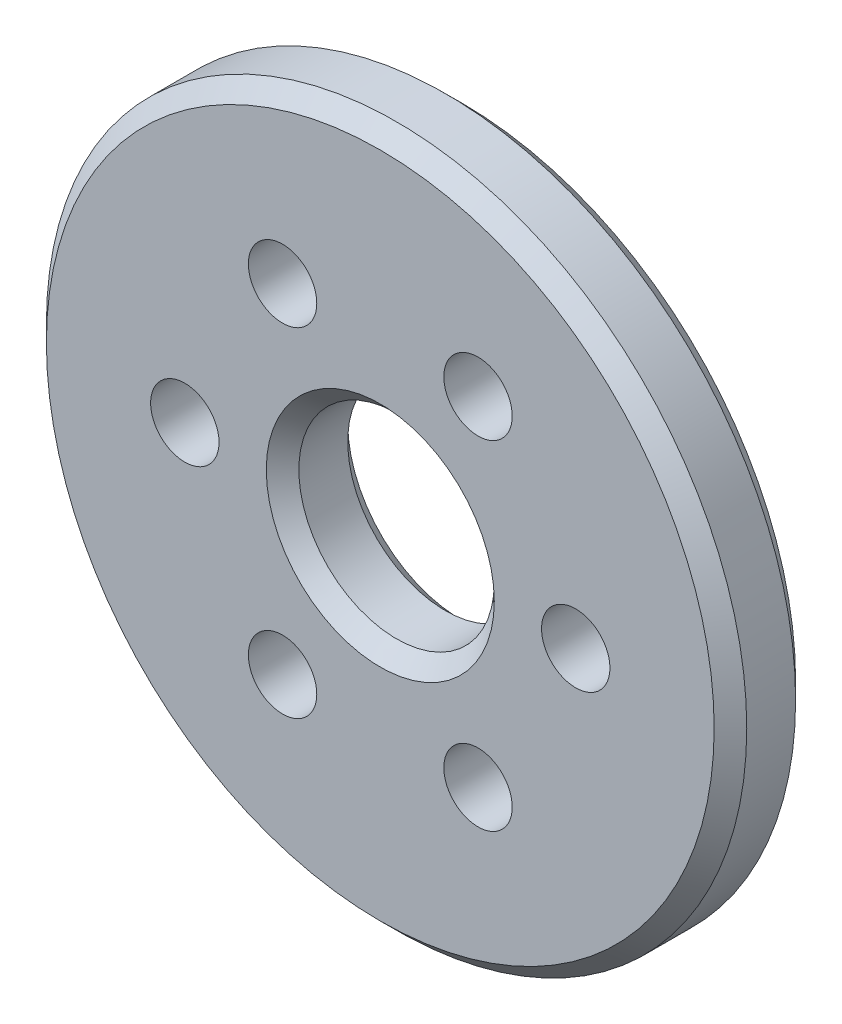
SolidWorks part; units mm, degrees
ref_plane "前视基准面" through (0, 0, 0) normal (0, 0, 1) x (1, 0, 0)
ref_plane "上视基准面" through (0, 0, 0) normal (0, 1, 0) x (1, 0, 0)
ref_plane "右视基准面" through (0, 0, 0) normal (1, 0, 0) x (0, 0, -1)
other "Configuration Table"
sketch "草图1" plane through (0, 0, 0) normal (0, 0, 1) x (1, 0, 0)
  line L0 (0, 0) -> (21.5, 0) construction
  circle A0 centre (0, 0) radius 21.5
  circle A1 centre (12, 0) radius 2.1
  circle A2 centre (6, -10.3923) radius 2.1
  circle A3 centre (-6, -10.3923) radius 2.1
  circle A4 centre (-12, 0) radius 2.1
  circle A5 centre (-6, 10.3923) radius 2.1
  circle A6 centre (6, 10.3923) radius 2.1
  circle A7 centre (0, 0) radius 6
  dimension "D1" = 43
  dimension "D2" = 4.2
  dimension "D5" = 12
  dimension "D3" = 12
  dimension "D4" = 6
extrude "凸台-拉伸1" add sketch "草图1" along normal blind 5
chamfer "倒角1" distance 1 angle 45 4 edges at (6, 0, 0) (6, 0, 5) (21.5, 0, 0) (21.5, 0, 5)
